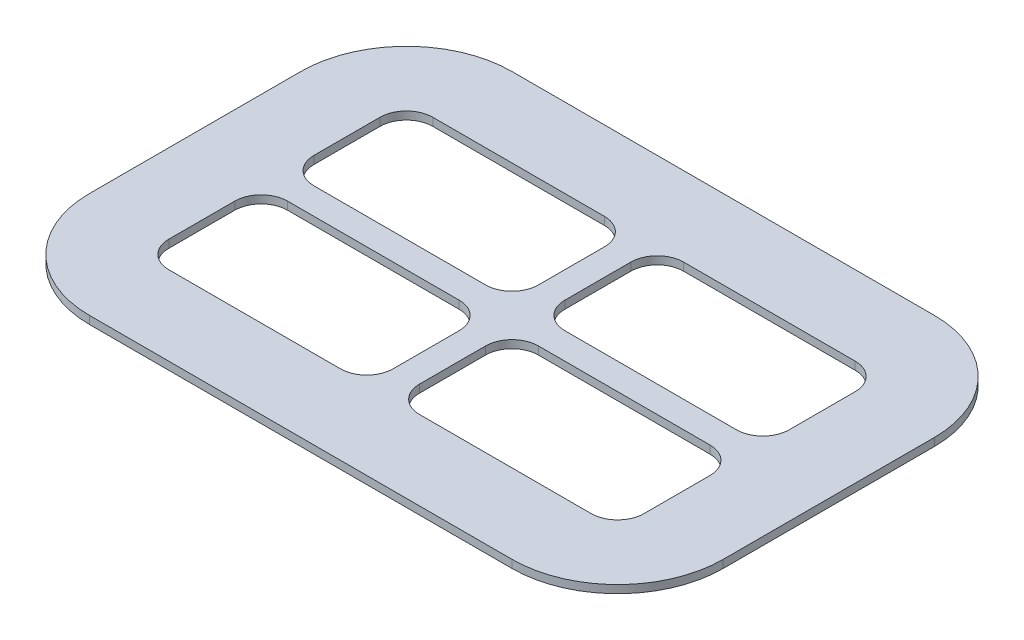
SolidWorks part; units mm, degrees
ref_plane "Plano frontal" through (0, 0, 0) normal (0, 0, 1) x (1, 0, 0)
ref_plane "Plano superior" through (0, 0, 0) normal (0, 1, 0) x (1, 0, 0)
ref_plane "Plano direito" through (0, 0, 0) normal (1, 0, 0) x (0, 0, -1)
sketch "Esboço1" plane through (0, 0, 0) normal (0, 1, 0) x (1, 0, 0)
  line L1 (120, -80) -> (-120, -80)
  line L2 (120, -80) -> (120, 80)
  line L3 (120, 80) -> (-120, 80)
  line L4 (-120, -80) -> (-120, 80)
  line L5 (120, -80) -> (-120, 80) construction
  line L6 (120, 80) -> (-120, -80) construction
  point P0 (0, 0)
  dimension "D1" = 240
  dimension "D2" = 160
extrude "Ressalto-extrusão1" add sketch "Esboço1" along normal blind 3
sketch "Esboço2" plane through (0, 3, 0) normal (0, 1, 0) x (1, 0, 0)
  line L4 (-90, -5) -> (-90, -50)
  line L5 (90, 5) -> (90, 50)
  line L6 (-5, 50) -> (-90, 50)
  line L7 (-5, -50) -> (-5, -5)
  line L8 (-90, 50) -> (-90, -50)
  line L9 (-90, -50) -> (90, -50)
  line L10 (90, -50) -> (90, 50)
  line L11 (90, 50) -> (-90, 50)
  line L12 (-90, 50) -> (-90, 5)
  line L13 (-90, -50) -> (-5, -50)
  line L14 (90, -50) -> (90, -5)
  line L15 (90, 50) -> (5, 50)
  line L16 (-90, 5) -> (-5, 5)
  line L17 (5, -50) -> (5, -5)
  line L18 (-90, -5) -> (-5, -5)
  line L19 (5, -50) -> (90, -50)
  line L20 (-5, 5) -> (-5, 50)
  line L24 (5, 5) -> (5, 50)
  line L26 (5, 5) -> (90, 5)
  line L28 (5, -5) -> (90, -5)
  dimension "D1" = 30
extrude "Corte-extrusão1" cut sketch "Esboço2" against normal through all
fillet "Filete1" radius 40 4 edges at (120, 1.5, 80) (-120, 1.5, 80) (-120, 1.5, -80) (120, 1.5, -80)
fillet "Filete2" radius 10 16 edges at (5, 1.5, 50) (-90, 1.5, 50) (-90, 1.5, -5) (5, 1.5, -5) (5, 1.5, 5) (5, 1.5, -50) (-90, 1.5, 5) (-5, 1.5, 5) (90, 1.5, -50) (90, 1.5, 5) (-5, 1.5, 50) (90, 1.5, -5) (90, 1.5, 50) (-5, 1.5, -5) (-5, 1.5, -50) (-90, 1.5, -50)
